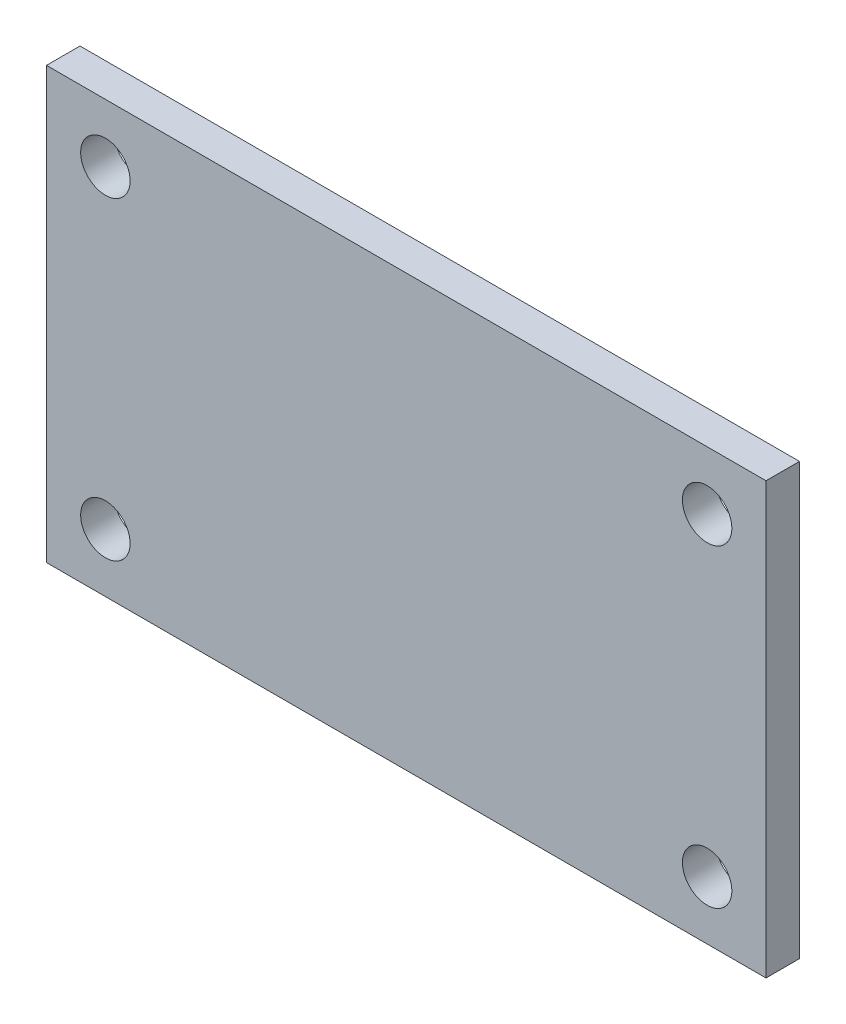
SolidWorks part; units mm, degrees
ref_plane "Front Plane" through (0, 0, 0) normal (0, 0, 1) x (1, 0, 0)
ref_plane "Top Plane" through (0, 0, 0) normal (0, 1, 0) x (1, 0, 0)
ref_plane "Right Plane" through (0, 0, 0) normal (1, 0, 0) x (0, 0, -1)
sketch "Sketch1" plane through (0, 0, 0) normal (0, 0, 1) x (1, 0, 0)
  line L1 (-17.4625, 10.4521) -> (17.4625, 10.4521)
  line L2 (-17.4625, 10.4521) -> (-17.4625, -10.4521)
  line L3 (-17.4625, -10.4521) -> (17.4625, -10.4521)
  line L4 (17.4625, 10.4521) -> (17.4625, -10.4521)
  line L5 (-17.4625, 10.4521) -> (17.4625, -10.4521) construction
  line L6 (-17.4625, -10.4521) -> (17.4625, 10.4521) construction
  point P0 (0, 0)
  dimension "D1" = 34.925
  dimension "D2" = 20.9042
extrude "Boss-Extrude1" add sketch "Sketch1" along normal mid plane 1.6256
sketch "Sketch2" plane through (0, 0, 0.8128) normal (0, 0, 1) x (1, 0, 0)
  line L0 (-17.4625, 0) -> (17.4625, 0) construction
  line L1 (-17.4625, 10.4521) -> (-17.4625, -10.4521) construction
  line L2 (17.4625, -10.4521) -> (17.4625, 10.4521) construction
  line L3 (0, 10.4521) -> (0, -10.4521) construction
  line L4 (17.4625, 10.4521) -> (-17.4625, 10.4521) construction
  line L5 (-17.4625, -10.4521) -> (17.4625, -10.4521) construction
  point P0 (-14.605, 7.62)
  point P1 (-14.605, -7.62)
  point P2 (14.605, -7.62)
  point P3 (14.605, 7.62)
  dimension "D1" = 15.24
  dimension "D2" = 29.21
hole_wizard "M2 Clearance Hole1" positions "Sketch3" profile "Sketch4" hole size "M2" standard "ANSI Metric" end condition up to next
sketch "Sketch3" plane through (0, 0, 0.8128) normal (0, 0, 1) x (1, 0, 0)
  point P0 (-14.605, 7.62)
  point P3 (14.605, 7.62)
  point P6 (14.605, -7.62)
  point P9 (-14.605, -7.62)
sketch "Sketch4" plane through (-14.605, 7.62, 0.8128) normal (1, 0, 0) x (0, -1, 0)
  line L0 (0, 0) -> (0, 1.6256)
  line L1 (0, 1.6256) -> (1.2, 1.6256)
  line L2 (1.2, 1.6256) -> (1.2, 0)
  line L5 (1.2, 0) -> (0, 0)
  line L11 (0, -6.35) -> (0, 107.95) construction
  dimension "Thru Hole Dia." = 2.4
  dimension "Thru Hole Depth" = 1.6256
